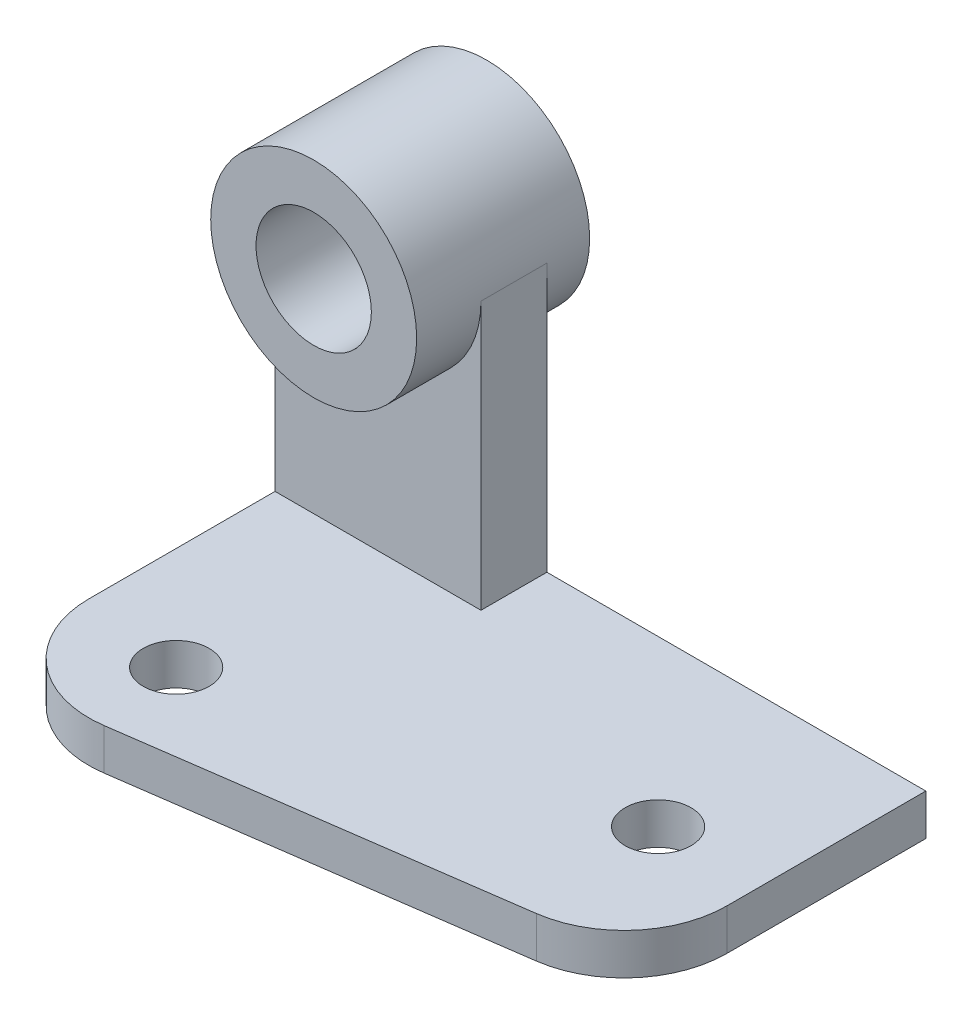
SolidWorks part; units mm, degrees
ref_plane "Front Plane" through (0, 0, 0) normal (0, 0, 1) x (1, 0, 0)
ref_plane "Top Plane" through (0, 0, 0) normal (0, 1, 0) x (1, 0, 0)
ref_plane "Right Plane" through (0, 0, 0) normal (1, 0, 0) x (0, 0, -1)
sketch "Sketch1" plane through (0, 0, 0) normal (0, 1, 0) x (1, 0, 0)
  line L0 (-71, 0) -> (71, 0) construction
  line L1 (0, 30.6161) -> (-71, 30.6161)
  line L2 (-71, 30.6161) -> (-71, -30.6161)
  line L3 (-42.5133, -55.3717) -> (49.4867, -42.414)
  line L4 (71, -17.6583) -> (71, 30.6161)
  line L5 (71, 30.6161) -> (0, 30.6161)
  arc A0 (-71, -30.6161) -> (-42.5133, -55.3717) centre (-46, -30.6161) ccw
  arc A1 (49.4867, -42.414) -> (71, -17.6583) centre (46, -17.6583) ccw
  circle A2 centre (46, -9.3839) radius 8
  circle A3 centre (-46, -34.3839) radius 8
  point P3 (0, 0)
  point P10 (-71, 0)
  point P13 (-71, -59.3839)
  point P16 (71, -39.3839)
  point P22 (71, -15.5312)
  point P23 (-59.2236, -36.6947)
  dimension "D4" = 25
  dimension "D5" = 16
  dimension "D1" = 142
  dimension "D2" = 70
  dimension "D3" = 90
  dimension "D6" = 40
  dimension "D7" = 25
  dimension "D8" = 25
  dimension "D9" = 92
extrude "Boss-Extrude1" add sketch "Sketch1" along normal blind 10
sketch "Sketch2" plane through (0, 0, 0) normal (0, 0, 1) x (1, 0, 0)
  line L0 (71, 10) -> (-71, 10) construction
  line L1 (-46, 7.6055) -> (-46, 75) construction
  line L2 (-71, 75) -> (-71, 7.6055) construction
  circle A0 centre (-46, 75) radius 25
  circle A1 centre (-46, 75) radius 14
  dimension "D1" = 50
  dimension "D2" = 28
  dimension "D4" = 65
  dimension "D3" = 117
extrude "Boss-Extrude2" add sketch "Sketch2" against normal blind 41 and the other way blind 1 separate body
sketch "Sketch3" plane through (0, 0, -30.6161) normal (0, 0, -1) x (-1, 0, 0)
  line L3 (-71, 10) -> (71, 10) construction
  line L4 (21, 10) -> (71, 10)
  line L5 (71, 75) -> (71, 10)
  line L6 (21, 75) -> (21, 10)
  circle A0 centre (46, 75) radius 25 construction
  arc A1 (21, 75) -> (71, 75) centre (46, 75) ccw
extrude "Boss-Extrude3" add sketch "Sketch3" against normal blind 16
sketch "Sketch5" plane through (0, 0, -30.6161) normal (0, 0, -1) x (-1, 0, 0)
  line L0 (21, 50) -> (-55.36, 50)
  line L1 (-55.36, 50) -> (-71, 10)
  line L5 (-71, 0) -> (71, 0)
  line L6 (71, 0) -> (71, 75)
  line L7 (21, 75) -> (21, 10)
  line L8 (21, 10) -> (-71, 10)
  line L9 (-71, 10) -> (-71, 0)
  line L12 (21, 50) -> (21, 10)
  line L13 (21, 10) -> (-71, 10)
  arc A1 (21, 75) -> (71, 75) centre (46, 75) ccw
  point P11 (-46.7704, 50)
  dimension "D2" = 40
  dimension "D3" = 76.36
  dimension "D1" = 0
